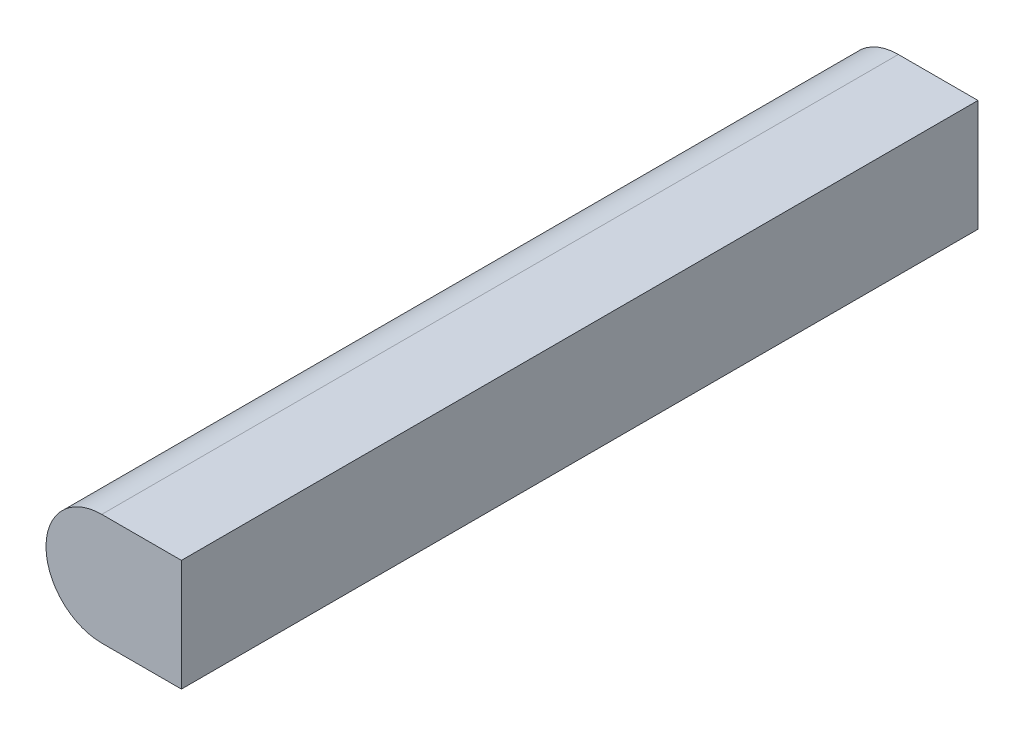
SolidWorks part; units mm, degrees
ref_plane "前视基准面" through (0, 0, 0) normal (0, 0, 1) x (1, 0, 0)
ref_plane "上视基准面" through (0, 0, 0) normal (0, 1, 0) x (1, 0, 0)
ref_plane "右视基准面" through (0, 0, 0) normal (1, 0, 0) x (0, 0, -1)
sketch "草图1" plane through (0, 0, 0) normal (0, 0, 1) x (0, -1, 0)
  line L1 (0, 0) -> (14, 0)
  line L2 (0, 0) -> (0, 10)
  line L3 (0, 10) -> (14, 10)
  line L4 (14, 0) -> (14, 10)
  dimension "D1" = 14
  dimension "D2" = 10
extrude "凸台-拉伸2" add sketch "草图1" along normal blind 100
sketch "草图2" plane through (0, 0, 100) normal (0, 0, 1) x (1, 0, 0)
  line L1 (0, 0) -> (0, -14) construction
  circle A0 centre (0, -7) radius 7
extrude "凸台-拉伸3" add sketch "草图2" against normal blind 100
